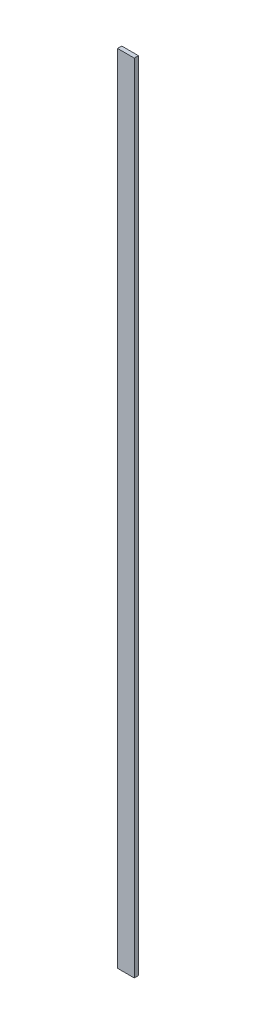
SolidWorks part; units mm, degrees
material "Spruce"
ref_plane "Front Plane" through (0, 0, 0) normal (0, 0, 1) x (1, 0, 0)
ref_plane "Top Plane" through (0, 0, 0) normal (0, 1, 0) x (1, 0, 0)
ref_plane "Right Plane" through (0, 0, 0) normal (1, 0, 0) x (0, 0, -1)
sketch "Sketch1" plane through (0, 0, 0) normal (0, 0, 1) x (1, 0, 0)
  line L0 (-7.6193, -72.566) -> (-13.9693, -72.566)
  line L4 (-7.6193, -72.566) -> (-7.6201, 229.6984)
  line L5 (-7.6201, 229.6984) -> (-13.9701, 229.6984)
  line L6 (-13.9701, 229.6984) -> (-13.9693, -72.566)
extrude "Boss-Extrude2" add sketch "Sketch1" along normal blind 1.5875
